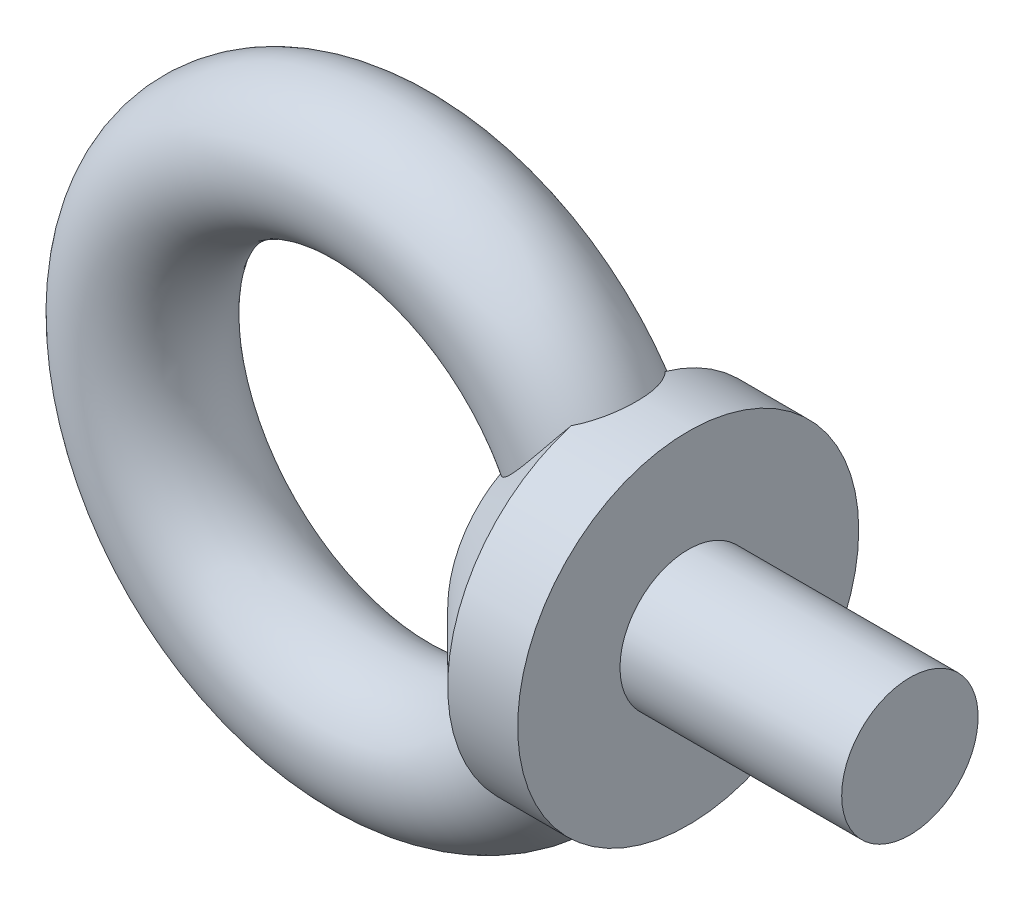
SolidWorks part; units mm, degrees
material "Galvanize Çelik"
ref_plane "Ön Düzlem" through (0, 0, 0) normal (0, 0, 1) x (1, 0, 0)
ref_plane "Üst Düzlem" through (0, 0, 0) normal (0, 1, 0) x (1, 0, 0)
ref_plane "Sağ Düzlem" through (0, 0, 0) normal (1, 0, 0) x (0, 0, -1)
sketch "Çizim1" plane through (0, 0, 0) normal (0, 0, 1) x (1, 0, 0)
  line L0 (10, 0) -> (14, 0) construction
  circle A0 centre (0, 0) radius 18 construction
  circle A1 centre (0, 0) radius 14
  circle A2 centre (0, 0) radius 10 construction
  dimension "D1" = 36
  dimension "D2" = 20
  dimension "D3" = 4
sketch "Çizim2" plane through (0, 0, 0) normal (0, 1, 0) x (1, 0, 0)
  line L0 (10, 0) -> (14, 0) construction
  line L1 (-14, 0) -> (14, 0) construction
  circle A0 centre (14, 0) radius 4
sweep "Süpür1" add profiles "Çizim2" path "Çizim1"
sketch "Çizim4" plane through (0, 0, 0) normal (1, 0, 0) x (0, 0, -1)
  circle A0 centre (0, 0) radius 10
  dimension "D1" = 20
extrude "Yükseklik-Ekstrüzyon1" add sketch "Çizim4" against normal blind 8.1 from offset 18
chamfer "Pah1" distance 4 angle 45 6 edges at (9.9, 14.9999, 0.4692) (14.9664, 9.9999, 0.0466) (9.9, -14.9995, -0.4719) (14.9664, -9.9999, -0.0466) (9.9, 0, 10) (9.9, 0, -10)
sketch "Çizim6" plane through (18, 0, 0) normal (1, 0, 0) x (0, 0, -1)
  circle A0 centre (0, 0) radius 4
  dimension "D1" = 8
extrude "Yükseklik-Ekstrüzyon2" add sketch "Çizim6" along normal blind 13
cosmetic thread "Kozmetik Diş Açma1" parameters "D2"=6.619
equation "\"D3@Çizim1\"=(\"D1@Çizim1\"-\"D2@Çizim1\")/4"
